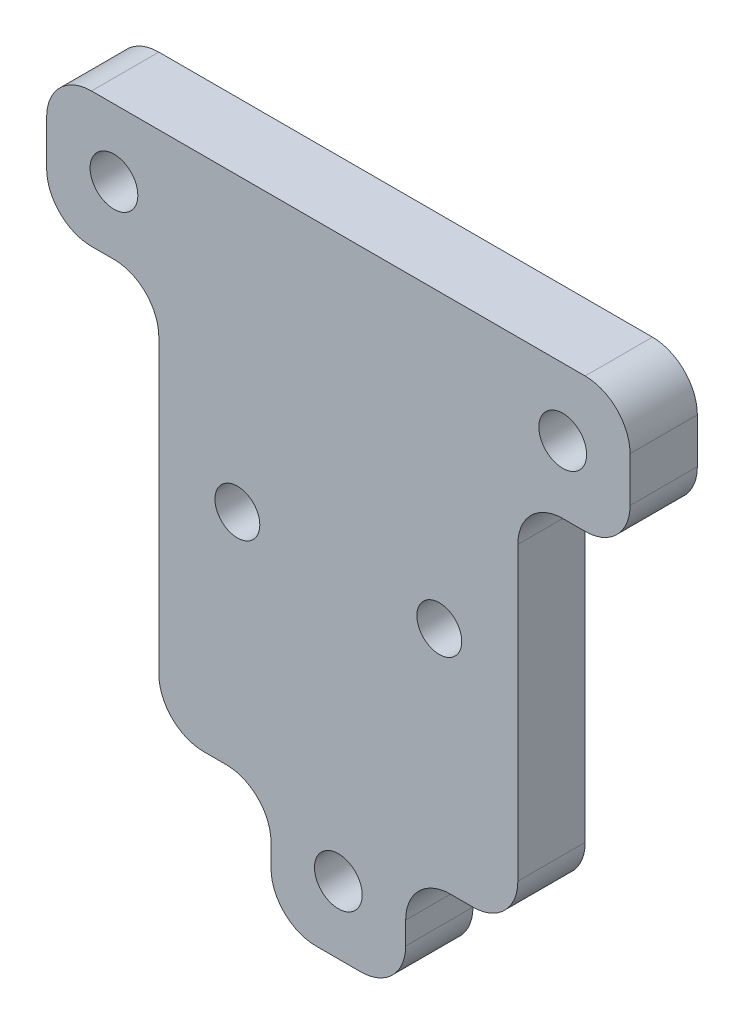
SolidWorks part; units mm, degrees
material "PE High Density"
ref_plane "Front Plane" through (0, 0, 0) normal (0, 0, 1) x (1, 0, 0)
ref_plane "Top Plane" through (0, 0, 0) normal (0, 1, 0) x (1, 0, 0)
ref_plane "Right Plane" through (0, 0, 0) normal (1, 0, 0) x (0, 0, -1)
sketch "Sketch1" plane through (0, 0, 0) normal (0, 0, 1) x (1, 0, 0)
  line L0 (25.4, 0) -> (25.4, 101.6) construction
  line L1 (0, 0) -> (50.8, 0)
  line L2 (0, 0) -> (0, 101.6)
  line L3 (0, 101.6) -> (50.8, 101.6)
  line L4 (50.8, 0) -> (50.8, 101.6)
  point P5 (12.9, 87.6)
  point P6 (37.9, 87.6)
  dimension "D1" = 25
  dimension "D2" = 14
  dimension "D3" = 50.8
  dimension "D4" = 101.6
extrude "Boss-Extrude1" add sketch "Sketch1" along normal blind 9.525
hole_wizard "Ø3.0 (3) Diameter Hole1" positions "Sketch2" profile "Sketch3" hole size "Ø3.0" standard "ANSI Metric" end condition through all
sketch "Sketch2" plane through (0, 0, 9.525) normal (0, 0, 1) x (1, 0, 0)
  point P0 (12.9, 87.6)
  point P3 (37.9, 87.6)
sketch "Sketch3" plane through (12.9, 87.6, 9.525) normal (1, 0, 0) x (0, -1, 0)
  line L0 (0, 0) -> (0, 9.525)
  line L1 (0, 9.525) -> (1.5, 9.525)
  line L2 (1.5, 9.525) -> (1.5, 0)
  line L5 (1.5, 0) -> (0, 0)
  line L11 (0, -6.35) -> (0, 107.95) construction
  dimension "Thru Hole Dia." = 3
  dimension "Thru Hole Depth" = 9.525
sketch "Sketch4" plane through (0, 0, 9.525) normal (0, 0, 1) x (1, 0, 0)
  line L0 (0, 101.6) -> (0, 0) construction
  line L1 (0, 73.025) -> (-15.875, 73.025)
  line L2 (0, 73.025) -> (0, 53.975)
  line L3 (0, 53.975) -> (-15.875, 53.975)
  line L4 (-15.875, 73.025) -> (-15.875, 53.975)
  line L5 (25.4, 0) -> (25.4, 101.6) construction
  line L6 (0, 0) -> (50.8, 0) construction
  line L7 (50.8, 101.6) -> (0, 101.6) construction
  line L8 (66.675, 73.025) -> (66.675, 53.975)
  line L9 (50.8, 53.975) -> (66.675, 53.975)
  line L10 (50.8, 73.025) -> (50.8, 53.975)
  line L11 (50.8, 73.025) -> (66.675, 73.025)
  line L13 (15.875, 0) -> (34.925, 0)
  line L14 (15.875, 0) -> (15.875, -15.875)
  line L15 (15.875, -15.875) -> (34.925, -15.875)
  line L16 (34.925, 0) -> (34.925, -15.875)
  point P12 (0, 63.5)
  point P13 (50.8, 63.5)
  dimension "D1" = 63.5
  dimension "D2" = 15.875
  dimension "D3" = 19.05
extrude "Boss-Extrude2" add sketch "Sketch4" against normal up to surface (9.525 mm away) up to face at (14.4, 87.6, 0)
hole_wizard "1/4 Clearance Hole1" positions "Sketch5" profile "Sketch6" hole size "1/4" standard "ANSI Inch" end condition through all
sketch "Sketch5" plane through (0, 0, 9.525) normal (0, 0, 1) x (1, 0, 0)
  line L0 (-15.875, 63.5) -> (66.675, 63.5) construction
  line L1 (-15.875, 73.025) -> (-15.875, 53.975) construction
  line L2 (66.675, 53.975) -> (66.675, 73.025) construction
  line L3 (25.4, -15.875) -> (25.4, 101.6) construction
  line L4 (15.875, -15.875) -> (34.925, -15.875) construction
  line L5 (50.8, 101.6) -> (0, 101.6) construction
  point P0 (-6.35, 63.5)
  point P2 (57.15, 63.5)
  point P4 (25.4, -6.35)
  dimension "D1" = 9.525
  dimension "D2" = 9.525
  dimension "D3" = 63.5
  dimension "D4" = 69.85
sketch "Sketch6" plane through (-6.35, 63.5, 9.525) normal (1, 0, 0) x (0, -1, 0)
  line L0 (0, 0) -> (0, 9.525)
  line L1 (0, 9.525) -> (3.3782, 9.525)
  line L2 (3.3782, 9.525) -> (3.3782, 0)
  line L5 (3.3782, 0) -> (0, 0)
  line L11 (0, -6.35) -> (0, 107.95) construction
  dimension "Thru Hole Dia." = 6.7564
  dimension "Thru Hole Depth" = 9.525
fillet "Fillet1" radius 6.35 16 edges at (0, 73.025, 4.7625) (-15.875, 73.025, 4.7625) (0, 0, 4.7625) (15.875, 0, 4.7625) (15.875, -15.875, 4.7625) (34.925, -15.875, 4.7625) (34.925, 0, 4.7625) (50.8, 0, 4.7625) (50.8, 53.975, 4.7625) (66.675, 53.975, 4.7625) (66.675, 73.025, 4.7625) (50.8, 73.025, 4.7625) (50.8, 101.6, 4.7625) (0, 101.6, 4.7625) (0, 53.975, 4.7625) (-15.875, 53.975, 4.7625)
sketch "Sketch7" plane through (0, 0, 9.525) normal (0, 0, 1) x (1, 0, 0)
  line L0 (44.45, 101.6) -> (6.35, 101.6) construction
  line L1 (-6.35, 73.025) -> (57.15, 73.025)
  line L2 (-6.35, 73.025) -> (-6.35, 101.6)
  line L3 (-6.35, 101.6) -> (57.15, 101.6)
  line L4 (57.15, 73.025) -> (57.15, 101.6)
  arc A0 (50.8, 79.375) -> (57.15, 73.025) centre (57.15, 79.375) ccw construction
extrude "Cut-Extrude1" cut sketch "Sketch7" against normal through all
hole_wizard "1/4 (0.25) Diameter Hole1" positions "Sketch8" profile "Sketch9" hole size "1/4" standard "ANSI Inch" end condition through all
sketch "Sketch8" plane through (0, 0, 9.525) normal (0, 0, 1) x (1, 0, 0)
  line L0 (25.4, -15.875) -> (25.4, 73.025) construction
  line L1 (22.225, -15.875) -> (28.575, -15.875) construction
  line L2 (60.325, 73.025) -> (-9.525, 73.025) construction
  line L3 (41.275, 0) -> (44.45, 0) construction
  point P0 (11.1125, 31.75)
  point P13 (39.6875, 31.75)
  dimension "D1" = 31.75
  dimension "D2" = 28.575
sketch "Sketch9" plane through (11.1125, 31.75, 9.525) normal (1, 0, 0) x (0, -1, 0)
  line L0 (0, 0) -> (0, 9.525)
  line L1 (0, 9.525) -> (3.175, 9.525)
  line L2 (3.175, 9.525) -> (3.175, 0)
  line L5 (3.175, 0) -> (0, 0)
  line L11 (0, -6.35) -> (0, 107.95) construction
  dimension "Thru Hole Dia." = 6.35
  dimension "Thru Hole Depth" = 9.525
equation "\"D1@Sketch1\"=25mm"
equation "\"D2@Sketch1\"=14mm"
